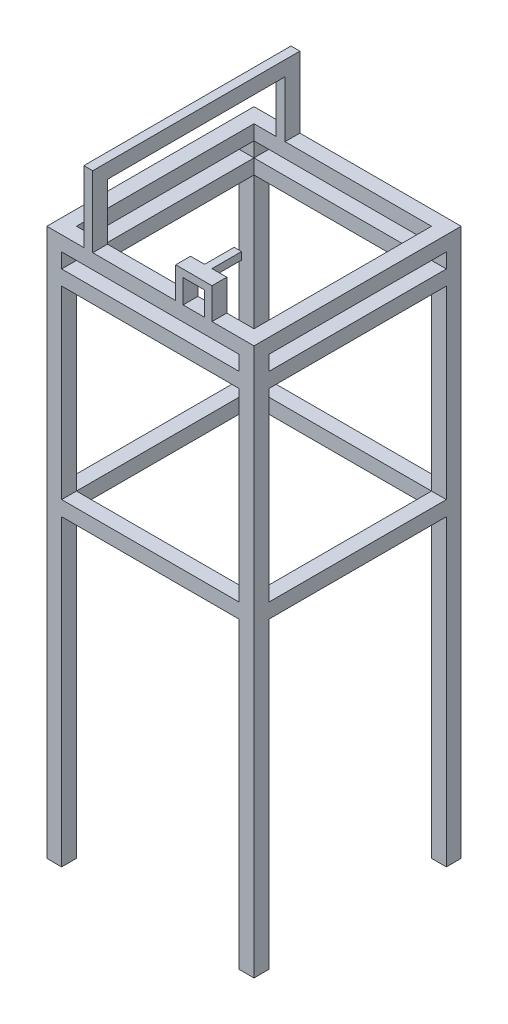
SolidWorks part; units mm, degrees
ref_plane "Alzado" through (0, 0, 0) normal (0, 0, 1) x (1, 0, 0)
ref_plane "Planta" through (0, 0, 0) normal (0, 1, 0) x (1, 0, 0)
ref_plane "Vista lateral" through (0, 0, 0) normal (1, 0, 0) x (0, 0, -1)
sketch "Croquis1" plane through (0, 0, 0) normal (0, 1, 0) x (1, 0, 0)
  line L1 (0, 0) -> (600, 0)
  line L2 (0, 0) -> (0, 600)
  line L3 (0, 600) -> (600, 600)
  line L4 (600, 0) -> (600, 600)
  line L5 (-50, -50) -> (650, -50)
  line L6 (-50, -50) -> (-50, 650)
  line L7 (-50, 650) -> (650, 650)
  line L8 (650, -50) -> (650, 650)
  dimension "D1" = 50
  dimension "D2" = 600
  dimension "D3" = 700
  dimension "D4" = 50
  dimension "D5" = 50
  dimension "D6" = 600
extrude "Saliente-Extruir1" add sketch "Croquis1" along normal blind 50
sketch "Croquis2" plane through (0, 0, 0) normal (0, -1, 0) x (1, 0, 0)
  line L0 (-50, -650) -> (-50, 50) construction
  line L1 (600, 0) -> (650, 0)
  line L2 (600, 0) -> (600, 50)
  line L3 (600, 50) -> (650, 50)
  line L4 (650, 0) -> (650, 50)
  line L5 (0, 0) -> (-50, 0)
  line L6 (0, 0) -> (0, 50)
  line L7 (0, 50) -> (-50, 50)
  line L8 (-50, 0) -> (-50, 50)
  line L9 (650, -650) -> (-50, -650) construction
  line L10 (0, -600) -> (-50, -600)
  line L11 (0, -600) -> (0, -650)
  line L12 (0, -650) -> (-50, -650)
  line L13 (-50, -600) -> (-50, -650)
  line L14 (600, -600) -> (650, -600)
  line L15 (600, -600) -> (600, -650)
  line L16 (600, -650) -> (650, -650)
  line L17 (650, -600) -> (650, -650)
extrude "Saliente-Extruir2" add sketch "Croquis2" along normal blind 1800
ref_plane "Plano1" through (0, -725, 0) normal (0, -1, 0) x (-1, 0, 0)
sketch "Croquis3" plane through (0, -725, 0) normal (0, -1, 0) x (-1, 0, 0)
  line L1 (50, -50) -> (-650, -50)
  line L2 (50, -50) -> (50, 650)
  line L3 (50, 650) -> (-650, 650)
  line L4 (-650, -50) -> (-650, 650)
  line L5 (0, 0) -> (-600, 0)
  line L6 (0, 0) -> (0, 600)
  line L7 (0, 600) -> (-600, 600)
  line L8 (-600, 0) -> (-600, 600)
extrude "Saliente-Extruir3" add sketch "Croquis3" along normal blind 50
ref_plane "Plano2" through (0, -50, 0) normal (0, -1, 0) x (-1, 0, 0)
sketch "Croquis4" plane through (0, -50, 0) normal (0, -1, 0) x (-1, 0, 0)
  line L1 (50, -50) -> (-650, -50)
  line L2 (50, -50) -> (50, 650)
  line L3 (50, 650) -> (-650, 650)
  line L4 (-650, -50) -> (-650, 650)
  line L5 (-600, 600) -> (0, 600)
  line L6 (-600, 600) -> (-600, 0)
  line L7 (-600, 0) -> (0, 0)
  line L8 (0, 600) -> (0, 0)
extrude "Saliente-Extruir4" add sketch "Croquis4" along normal blind 50
sketch "Croquis6" plane through (0, 0, 50) normal (0, 0, 1) x (1, 0, 0)
  line L0 (0, 50) -> (600, 50) construction
  line L1 (-50, 50) -> (650, 50) construction
  line L2 (0, 0) -> (600, 0) construction
  line L3 (508.0069, 0) -> (385.4762, 0)
  line L4 (508.0069, 0) -> (508.0069, 155)
  line L5 (508.0069, 155) -> (385.4762, 155)
  line L6 (385.4762, 0) -> (385.4762, 155)
  line L8 (483.0069, 50) -> (410.4762, 50)
  line L9 (483.0069, 50) -> (483.0069, 130)
  line L10 (483.0069, 130) -> (410.4762, 130)
  line L11 (410.4762, 50) -> (410.4762, 130)
  point P14 (446.7416, 130)
  dimension "D1" = 25
  dimension "D2" = 25
  dimension "D3" = 25
  dimension "D4" = 80
extrude "Saliente-Extruir5" add sketch "Croquis6" against normal blind 50
sketch "Croquis7" plane through (0, 0, 0) normal (0, 0, -1) x (-1, 0, 0)
  line L0 (-410.4762, 130) -> (-483.0069, 130) construction
  line L1 (-483.0069, 130) -> (-483.0069, 155) construction
  line L2 (-508.0069, 155) -> (-385.4762, 155) construction
  line L3 (-483.0069, 155) -> (-410.4762, 155) construction
  line L4 (-410.4762, 155) -> (-410.4762, 130) construction
  line L6 (-432.9762, 130) -> (-457.9762, 130)
  line L7 (-432.9762, 130) -> (-432.9762, 155)
  line L8 (-432.9762, 155) -> (-457.9762, 155)
  line L9 (-457.9762, 130) -> (-457.9762, 155)
  dimension "D1" = 25
  dimension "D2" = 22.5
extrude "Saliente-Extruir6" add sketch "Croquis7" along normal blind 100
ref_plane "Plano3" through (90, 0, 0) normal (-1, 0, 0) x (0, 0, 1)
sketch "Croquis9" plane through (90, 0, 0) normal (-1, 0, 0) x (0, 0, 1)
  line L0 (0, 50) -> (50, 50)
  line L1 (-650, 50) -> (-600, 50)
  line L2 (-650, 50) -> (-650, 290)
  line L3 (-650, 290) -> (50, 290)
  line L4 (50, 50) -> (50, 290)
  line L11 (-600, 50) -> (-600, 240)
  line L12 (-600, 240) -> (0, 240)
  line L13 (0, 50) -> (0, 240)
  dimension "D1" = 240
  dimension "D2" = 50
extrude "Saliente-Extruir7" add sketch "Croquis9" along normal mid plane 30 from offset 0
